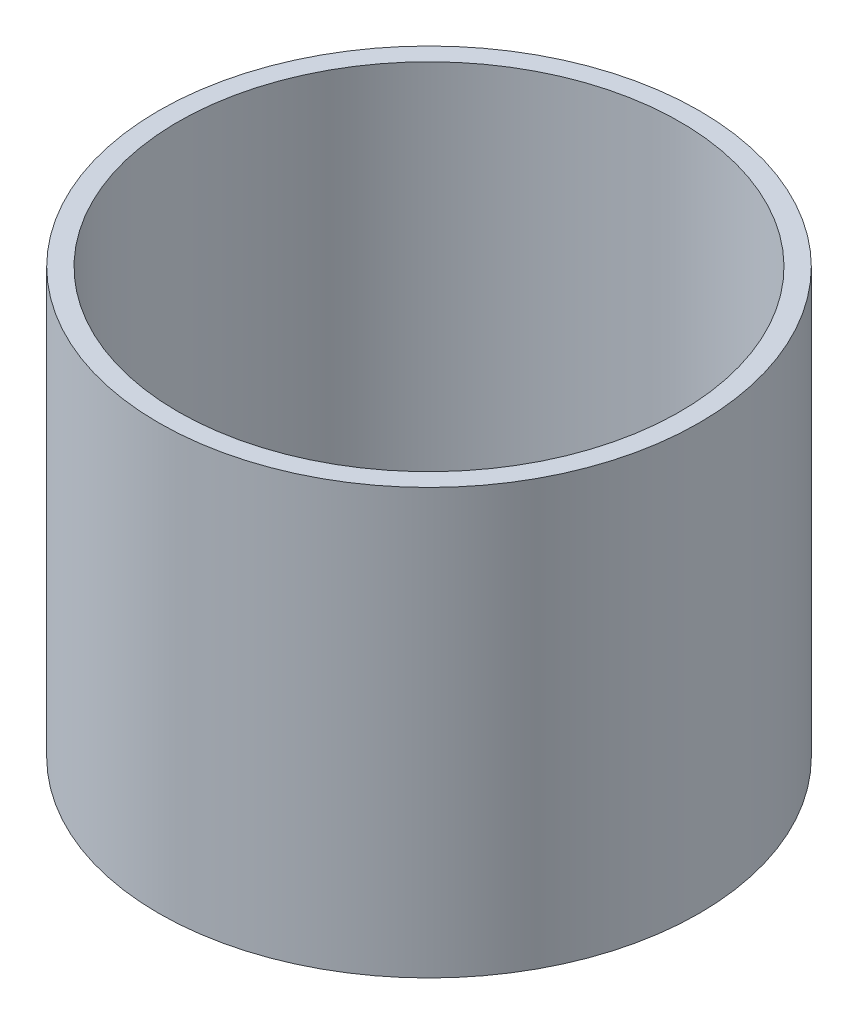
SolidWorks part; units mm, degrees
ref_plane "Front Plane" through (0, 0, 0) normal (0, 0, 1) x (1, 0, 0)
ref_plane "Top Plane" through (0, 0, 0) normal (0, 1, 0) x (1, 0, 0)
ref_plane "Right Plane" through (0, 0, 0) normal (1, 0, 0) x (0, 0, -1)
sketch "Sketch1" plane through (0, 0, 0) normal (0, 1, 0) x (1, 0, 0)
  circle A0 centre (0, 0) radius 17.78
extrude "Boss-Extrude1" add sketch "Sketch1" along normal blind 27.94
sketch "Sketch2" plane through (0, 27.94, 0) normal (0, 1, 0) x (1, 0, 0)
  circle A0 centre (0, 0) radius 16.51
extrude "Cut-Extrude1" cut sketch "Sketch2" against normal through all
